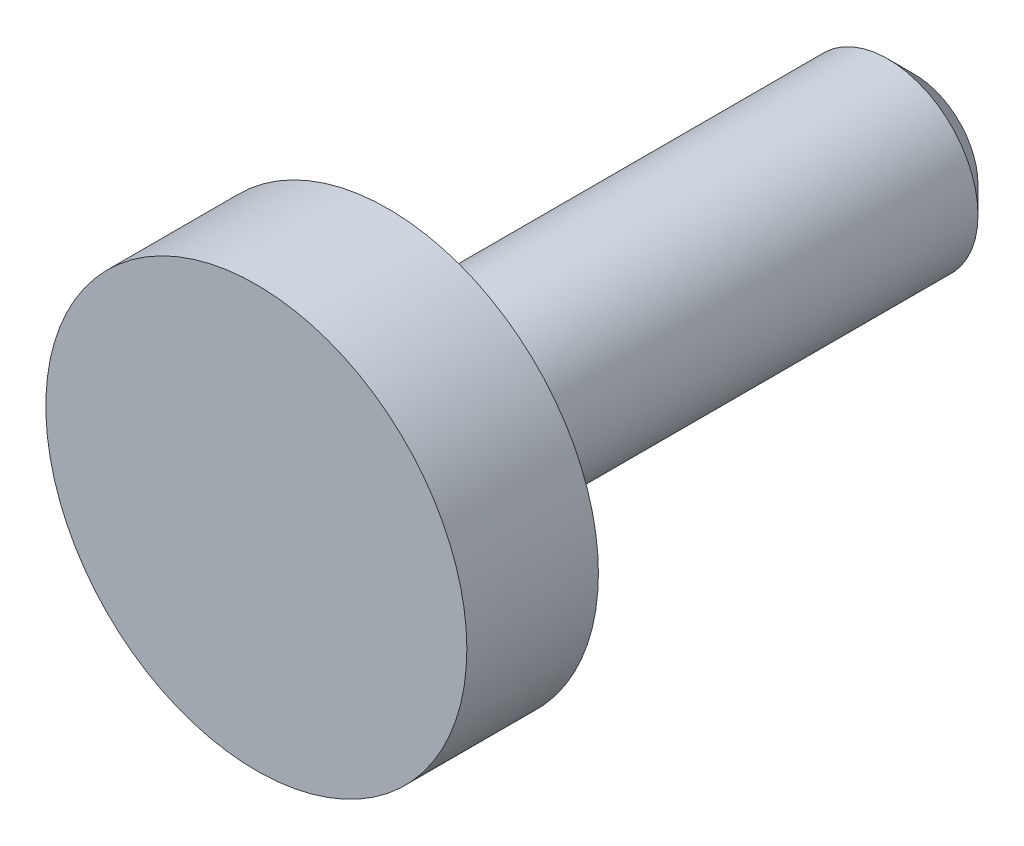
SolidWorks part; units mm, degrees
ref_plane "Front Plane" through (0, 0, 0) normal (0, 0, 1) x (1, 0, 0)
ref_plane "Top Plane" through (0, 0, 0) normal (0, 1, 0) x (1, 0, 0)
ref_plane "Right Plane" through (0, 0, 0) normal (1, 0, 0) x (0, 0, -1)
sketch "Sketch1" plane through (0, 0, 0) normal (0, 0, 1) x (1, 0, 0)
  circle A0 centre (0, 0) radius 3.425
  dimension "D1" = 6.85
extrude "Boss-Extrude1" add sketch "Sketch1" along normal blind 20
sketch "Sketch2" plane through (0, 0, 20) normal (0, 0, 1) x (1, 0, 0)
  circle A0 centre (0, 0) radius 8
  dimension "D1" = 16
extrude "Boss-Extrude3" add sketch "Sketch2" along normal blind 5 contours A0
chamfer "Chamfer1" distance 1 angle 45 1 edges at (3.425, 0, 0)
